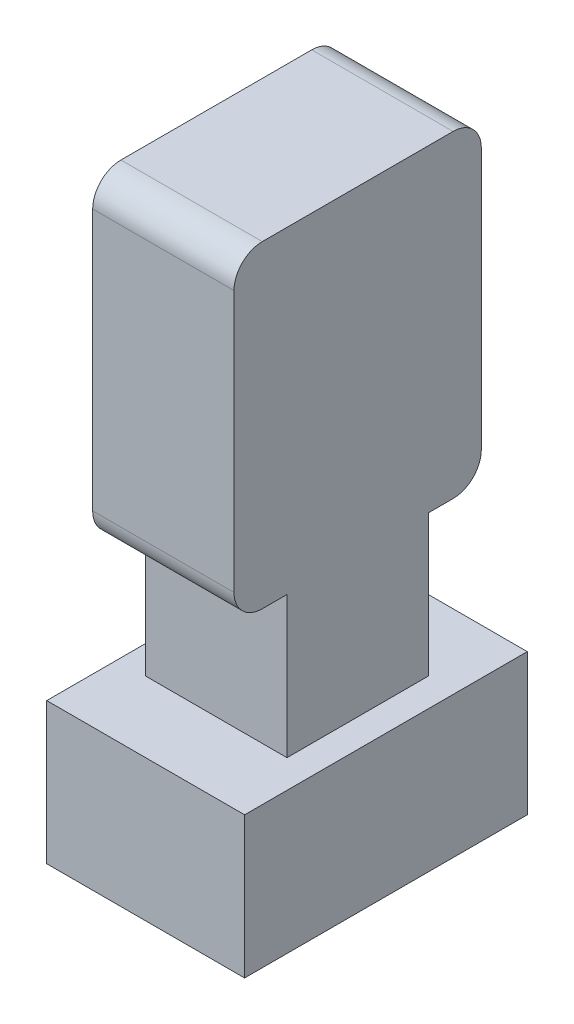
SolidWorks part; units mm, degrees
ref_plane "Front Plane" through (0, 0, 0) normal (0, 0, 1) x (1, 0, 0)
ref_plane "Top Plane" through (0, 0, 0) normal (0, 1, 0) x (1, 0, 0)
ref_plane "Right Plane" through (0, 0, 0) normal (1, 0, 0) x (0, 0, -1)
sketch "Sketch1" plane through (0, 0, 0) normal (0, 1, 0) x (1, 0, 0)
  line L1 (0, 0) -> (14, 0)
  line L2 (0, 0) -> (0, 20)
  line L3 (0, 20) -> (14, 20)
  line L4 (14, 0) -> (14, 20)
  dimension "D1" = 20
  dimension "D2" = 14
extrude "Boss-Extrude1" add sketch "Sketch1" along normal blind 10
sketch "Sketch2" plane through (0, 10, 0) normal (0, 1, 0) x (1, 0, 0)
  line L1 (2, 15) -> (12, 15)
  line L2 (2, 15) -> (2, 5)
  line L3 (2, 5) -> (12, 5)
  line L4 (12, 15) -> (12, 5)
  line L5 (2, 15) -> (12, 5) construction
  line L6 (2, 5) -> (12, 15) construction
  line L8 (14, 10) -> (7, 10) construction
  line L9 (14, 0) -> (14, 20) construction
  line L10 (7, 10) -> (7, 0) construction
  line L11 (0, 0) -> (14, 0) construction
  point P0 (7, 10)
  dimension "D1" = 10
  dimension "D2" = 10
extrude "Boss-Extrude2" add sketch "Sketch2" along normal blind 10
ref_plane "Plane1" through (7, 0, 0) normal (1, 0, 0) x (0, 0, -1)
sketch "Sketch3" plane through (7, 0, 0) normal (1, 0, 0) x (0, 0, -1)
  line L1 (1.25, 22) -> (1.25, 40.5)
  line L2 (3.25, 42.5) -> (16.75, 42.5)
  line L3 (18.75, 40.5) -> (18.75, 22)
  line L4 (16.75, 20) -> (3.25, 20)
  line L5 (10, 20) -> (10, 0) construction
  line L6 (5, 20) -> (15, 20) construction
  line L7 (0, 0) -> (20, 0) construction
  arc A0 (16.75, 42.5) -> (18.75, 40.5) centre (16.75, 40.5) cw
  arc A1 (18.75, 22) -> (16.75, 20) centre (16.75, 22) cw
  arc A2 (3.25, 20) -> (1.25, 22) centre (3.25, 22) cw
  arc A3 (1.25, 40.5) -> (3.25, 42.5) centre (3.25, 40.5) cw
  point P8 (18.75, 42.5)
  point P18 (1.25, 20)
  point P21 (1.25, 42.5)
  dimension "D3" = 2
  dimension "D1" = 17.5
  dimension "D2" = 22.5
extrude "Boss-Extrude3" add sketch "Sketch3" along normal mid plane 10
